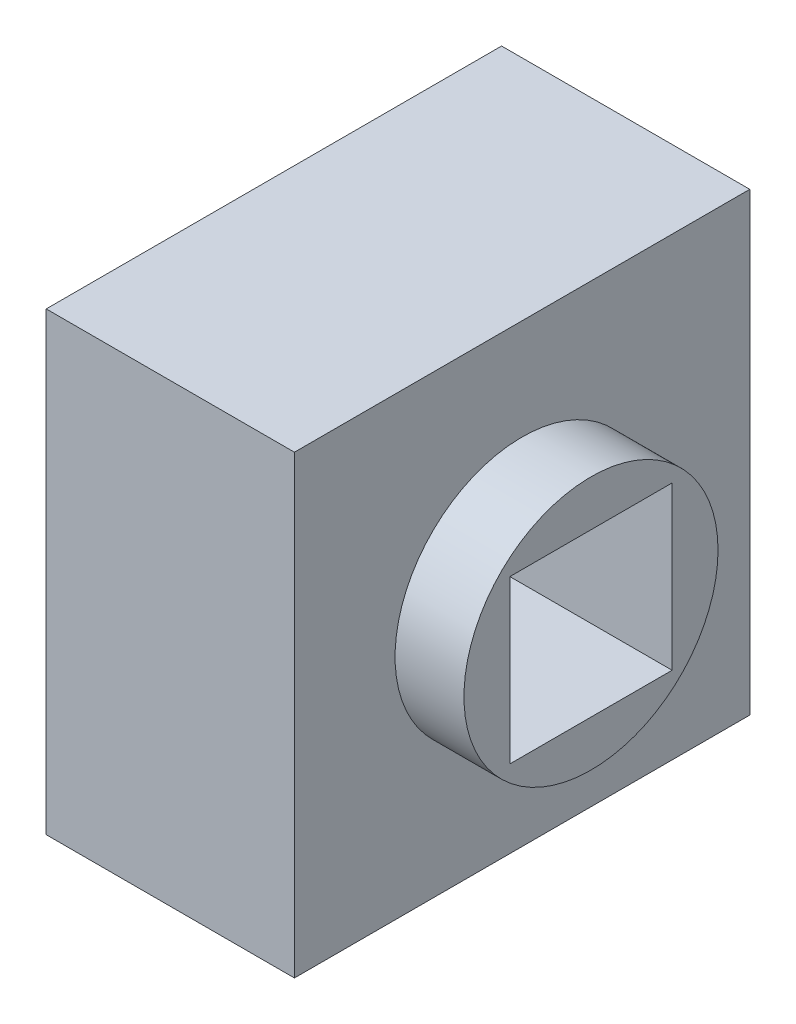
SolidWorks part; units mm, degrees
ref_plane "Front" through (0, 0, 0) normal (0, 0, 1) x (1, 0, 0)
ref_plane "Top" through (0, 0, 0) normal (0, 1, 0) x (1, 0, 0)
ref_plane "Right" through (0, 0, 0) normal (1, 0, 0) x (0, 0, -1)
sketch "Sketch2" plane through (0, 0, 0) normal (1, 0, 0) x (0, 0, -1)
  line L1 (0, 0) -> (8.3, 0)
  line L2 (0, 0) -> (0, 8.3)
  line L3 (0, 8.3) -> (8.3, 8.3)
  line L4 (8.3, 0) -> (8.3, 8.3)
  dimension "D1" = 8.3
  dimension "D2" = 8.3
extrude "Extrude-Thin1" add sketch "Sketch2" along normal blind 12.7 thin
sketch "Sketch3" plane through (12.7, 0, 0) normal (1, 0, 0) x (0, 0, -1)
  line L0 (0, 0) -> (8.3, 8.3) construction
  line L2 (0, 8.3) -> (8.3, 8.3)
  line L3 (0, 8.3) -> (0, 0)
  line L4 (0, 0) -> (8.3, 0)
  line L5 (8.3, 8.3) -> (8.3, 0)
  circle A0 centre (4.15, 4.15) radius 6.5
extrude "Boss-Extrude1" add sketch "Sketch3" along normal blind 3.525
